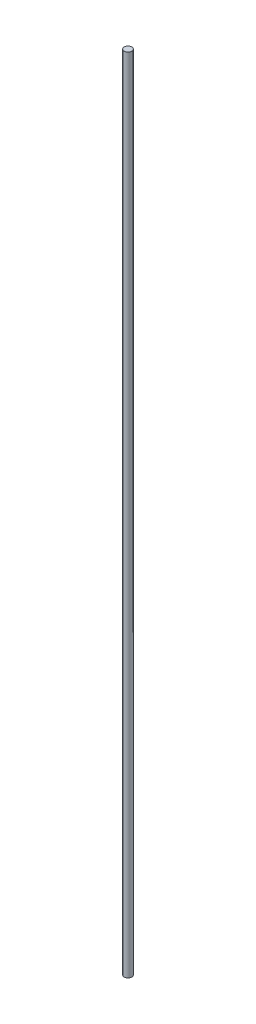
SolidWorks part; units mm, degrees
ref_plane "Front Plane" through (0, 0, 0) normal (0, 0, 1) x (1, 0, 0)
ref_plane "Top Plane" through (0, 0, 0) normal (0, 1, 0) x (1, 0, 0)
ref_plane "Right Plane" through (0, 0, 0) normal (1, 0, 0) x (0, 0, -1)
sketch "Sketch1" plane through (0, 0, 0) normal (0, 1, 0) x (1, 0, 0)
  circle A0 centre (0, 0) radius 9.5
  dimension "D1" = 19
extrude "Boss-Extrude1" add sketch "Sketch1" along normal blind 2025
